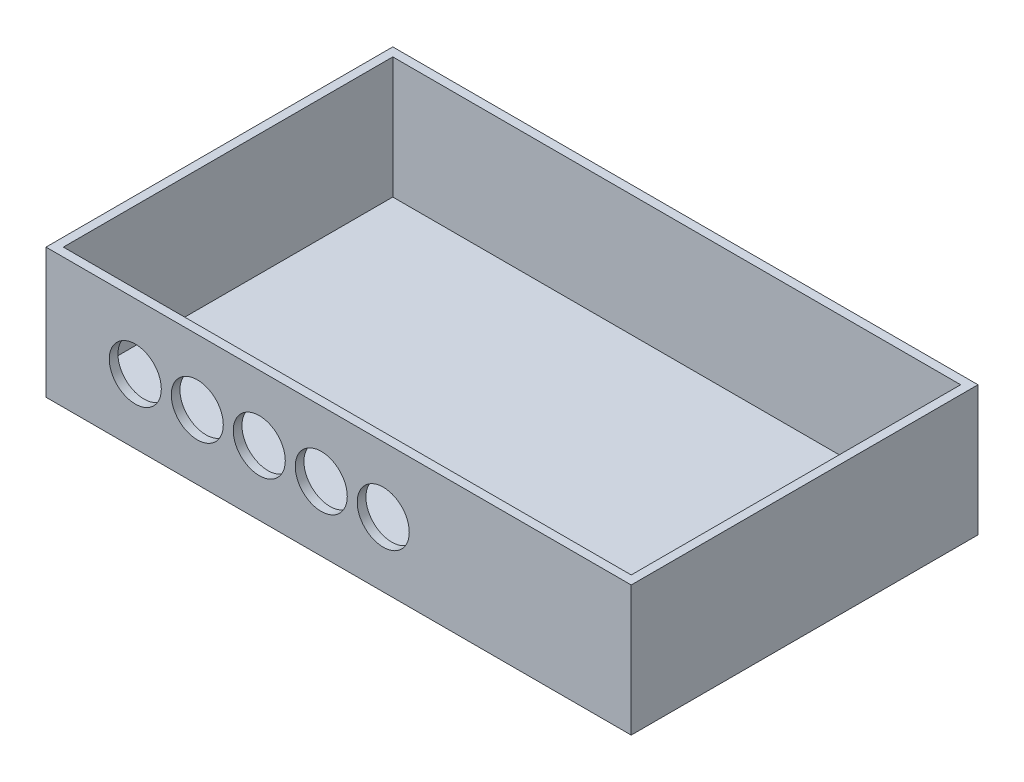
SolidWorks part; units mm, degrees
ref_plane "Ebene vorne" through (0, 0, 0) normal (0, 0, 1) x (1, 0, 0)
ref_plane "Ebene oben" through (0, 0, 0) normal (0, 1, 0) x (1, 0, 0)
ref_plane "Ebene rechts" through (0, 0, 0) normal (1, 0, 0) x (0, 0, -1)
sketch "Skizze1" plane through (0, 0, 0) normal (0, 1, 0) x (1, 0, 0)
  line L1 (0, 0) -> (135, 0)
  line L2 (0, 0) -> (0, 80)
  line L3 (0, 80) -> (135, 80)
  line L4 (135, 0) -> (135, 80)
  dimension "D1" = 80
  dimension "D2" = 135
extrude "Aufsatz-Linear austragen1" add sketch "Skizze1" along normal blind 30
shell "Schale1" thickness 2
sketch "Skizze2" plane through (0, 0, 0) normal (0, 0, 1) x (1, 0, 0)
  line L0 (4.8493, 14.94) -> (121.4088, 14.94) construction
  line L1 (0, 0) -> (135, 0) construction
  line L2 (0, 30) -> (0, 0) construction
  circle A0 centre (20.6, 14.94) radius 6
  circle A1 centre (34.9, 14.94) radius 6
  circle A2 centre (49.2, 14.94) radius 6
  circle A3 centre (63.5, 14.94) radius 6
  circle A4 centre (77.8, 14.94) radius 6
  dimension "D2" = 12
  dimension "D3" = 20.6
  dimension "D4" = 34.9
  dimension "D5" = 49.2
  dimension "D6" = 63.5
  dimension "D7" = 77.8
  dimension "D8" = 12
  dimension "D9" = 12
  dimension "D10" = 12
  dimension "D11" = 12
  dimension "D1" = 14.94
extrude "Schnitt-Linear austragen1" cut sketch "Skizze2" against normal blind 30
